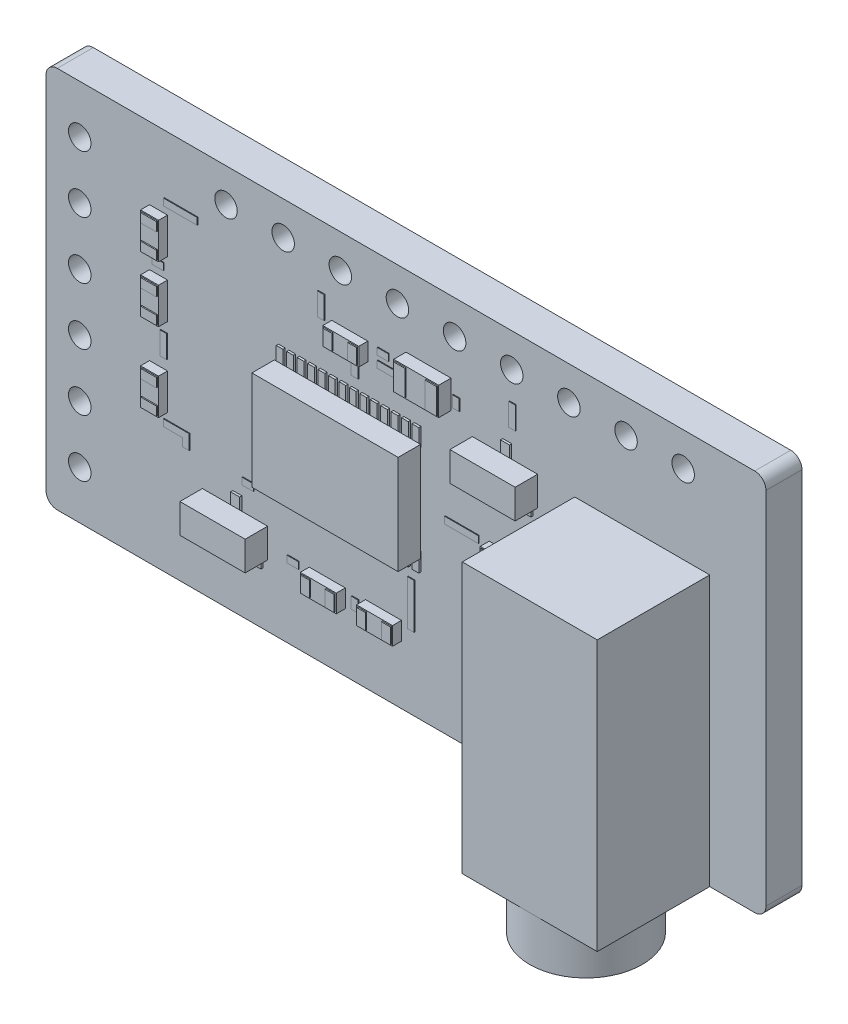
SolidWorks part; units mm, degrees
ref_plane "Front Plane" through (0, 0, 0) normal (0, 0, 1) x (1, 0, 0)
ref_plane "Top Plane" through (0, 0, 0) normal (0, 1, 0) x (1, 0, 0)
ref_plane "Right Plane" through (0, 0, 0) normal (1, 0, 0) x (0, 0, -1)
sketch "Sketch1" plane through (0, 0, 0) normal (0, 0, 1) x (1, 0, 0)
  line L0 (0.5, 0) -> (31.5, 0)
  line L1 (32, 0.5) -> (32, 16.5)
  line L2 (31.5, 17) -> (0.5, 17)
  line L3 (0, 16.5) -> (0, 0.5)
  arc A0 (31.5, 0) -> (32, 0.5) centre (31.5, 0.5) ccw
  arc A1 (32, 16.5) -> (31.5, 17) centre (31.5, 16.5) ccw
  arc A2 (0.5, 17) -> (0, 16.5) centre (0.5, 16.5) ccw
  arc A3 (0, 0.5) -> (0.5, 0) centre (0.5, 0.5) ccw
extrude "PCB" add sketch "Sketch1" along normal blind 1.6
ref_plane "Plane_z1_6" through (0, 0, 1.6) normal (0, 0, 1) x (1, 0, 0)
sketch "Sketch2" plane through (0, 0, 1.6) normal (0, 0, 1) x (1, 0, 0)
  line L0 (13.6, 11.75) -> (13.6, 12.25)
  line L1 (13.6, 12.25) -> (13.9, 12.25)
  line L2 (13.9, 12.25) -> (13.9, 11.75)
  line L3 (13.9, 11.75) -> (13.6, 11.75)
  line L4 (20.6, 13.25) -> (20.6, 14.25)
  line L5 (20.6, 14.25) -> (20.9, 14.25)
  line L6 (20.9, 14.25) -> (20.9, 13.25)
  line L7 (20.9, 13.25) -> (20.6, 13.25)
  line L8 (8.75, 5.4) -> (9.25, 5.4)
  line L9 (9.25, 5.4) -> (9.25, 5.1)
  line L10 (9.25, 5.1) -> (8.75, 5.1)
  line L11 (8.75, 5.1) -> (8.75, 5.4)
  line L12 (5.25, 5.9) -> (6.4, 5.9)
  line L13 (6.4, 5.9) -> (6.4, 5.25)
  line L14 (6.4, 5.25) -> (6.1, 5.25)
  line L15 (6.1, 5.25) -> (6.1, 5.6)
  line L16 (6.1, 5.6) -> (5.25, 5.6)
  line L17 (5.25, 5.6) -> (5.25, 5.9)
  line L18 (5.1, 8.25) -> (5.1, 9.25)
  line L19 (5.1, 9.25) -> (5.4, 9.25)
  line L20 (5.4, 9.25) -> (5.4, 8.25)
  line L21 (5.4, 8.25) -> (5.1, 8.25)
  line L22 (5.25, 11.6) -> (4.75, 11.6)
  line L23 (4.75, 11.6) -> (4.75, 11.9)
  line L24 (4.75, 11.9) -> (5.25, 11.9)
  line L25 (5.25, 11.9) -> (5.25, 11.6)
  line L26 (5.25, 14.4) -> (6.75, 14.4)
  line L27 (6.75, 14.4) -> (6.75, 14.1)
  line L28 (6.75, 14.1) -> (5.25, 14.1)
  line L29 (5.25, 14.1) -> (5.25, 14.4)
  line L30 (19.25, 8.1) -> (17.75, 8.1)
  line L31 (17.75, 8.1) -> (17.75, 8.4)
  line L32 (17.75, 8.4) -> (19.25, 8.4)
  line L33 (19.25, 8.4) -> (19.25, 8.1)
  line L34 (21.75, 8.4) -> (22.75, 8.4)
  line L35 (22.75, 8.4) -> (22.75, 8.1)
  line L36 (22.75, 8.1) -> (21.75, 8.1)
  line L37 (21.75, 8.1) -> (21.75, 8.4)
  line L38 (19.1, 6.25) -> (19.1, 7.25)
  line L39 (19.1, 7.25) -> (19.4, 7.25)
  line L40 (19.4, 7.25) -> (19.4, 6.25)
  line L41 (19.4, 6.25) -> (19.1, 6.25)
  line L42 (21.6, 6.25) -> (21.6, 7.25)
  line L43 (21.6, 7.25) -> (21.9, 7.25)
  line L44 (21.9, 7.25) -> (21.9, 6.25)
  line L45 (21.9, 6.25) -> (21.6, 6.25)
  line L46 (19.1, 4.25) -> (19.1, 5.25)
  line L47 (19.1, 5.25) -> (19.4, 5.25)
  line L48 (19.4, 5.25) -> (19.4, 4.25)
  line L49 (19.4, 4.25) -> (19.1, 4.25)
  line L50 (21.6, 4.25) -> (21.6, 5.25)
  line L51 (21.6, 5.25) -> (21.9, 5.25)
  line L52 (21.9, 5.25) -> (21.9, 4.25)
  line L53 (21.9, 4.25) -> (21.6, 4.25)
  line L54 (13.9, 3.25) -> (13.9, 2.75)
  line L55 (13.9, 2.75) -> (13.6, 2.75)
  line L56 (13.6, 2.75) -> (13.6, 3.25)
  line L57 (13.6, 3.25) -> (13.9, 3.25)
  line L58 (16.1, 3.25) -> (16.1, 5.25)
  line L59 (16.1, 5.25) -> (16.4, 5.25)
  line L60 (16.4, 5.25) -> (16.4, 3.25)
  line L61 (16.4, 3.25) -> (16.1, 3.25)
  line L62 (11.25, 3.1) -> (10.75, 3.1)
  line L63 (10.75, 3.1) -> (10.75, 3.4)
  line L64 (10.75, 3.4) -> (11.25, 3.4)
  line L65 (11.25, 3.4) -> (11.25, 3.1)
  line L66 (12.1, 13.25) -> (12.1, 14.25)
  line L67 (12.1, 14.25) -> (12.4, 14.25)
  line L68 (12.4, 14.25) -> (12.4, 13.25)
  line L69 (12.4, 13.25) -> (12.1, 13.25)
  line L70 (14.75, 13.4) -> (15.25, 13.4)
  line L71 (15.25, 13.4) -> (15.25, 13.1)
  line L72 (15.25, 13.1) -> (14.75, 13.1)
  line L73 (14.75, 13.1) -> (14.75, 13.4)
  line L74 (15.9, 13.25) -> (15.9, 12.6)
  line L75 (15.9, 12.6) -> (14.75, 12.6)
  line L76 (14.75, 12.6) -> (14.75, 12.9)
  line L77 (14.75, 12.9) -> (15.6, 12.9)
  line L78 (15.6, 12.9) -> (15.6, 13.25)
  line L79 (15.6, 13.25) -> (15.9, 13.25)
  line L80 (18.4, 13.25) -> (18.4, 12.75)
  line L81 (18.4, 12.75) -> (18.1, 12.75)
  line L82 (18.1, 12.75) -> (18.1, 13.25)
  line L83 (18.1, 13.25) -> (18.4, 13.25)
extrude "Tracks" add sketch "Sketch2" along normal blind 0.035
sketch "Sketch3" plane through (0, 0, 1.6) normal (0, 0, 1) x (1, 0, 0)
  line L1 (10.3321, 5.7) -> (10.6321, 5.7)
  line L2 (10.3321, 5.7) -> (10.3321, 6.5)
  line L3 (10.3321, 6.5) -> (10.6321, 6.5)
  line L4 (10.6321, 5.7) -> (10.6321, 6.5)
  line L6 (10.7964, 5.7) -> (11.0964, 5.7)
  line L7 (10.7964, 5.7) -> (10.7964, 6.5)
  line L8 (10.7964, 6.5) -> (11.0964, 6.5)
  line L9 (11.0964, 5.7) -> (11.0964, 6.5)
  line L11 (11.2607, 5.7) -> (11.5607, 5.7)
  line L12 (11.2607, 5.7) -> (11.2607, 6.5)
  line L13 (11.2607, 6.5) -> (11.5607, 6.5)
  line L14 (11.5607, 5.7) -> (11.5607, 6.5)
  line L16 (11.725, 5.7) -> (12.025, 5.7)
  line L17 (11.725, 5.7) -> (11.725, 6.5)
  line L18 (11.725, 6.5) -> (12.025, 6.5)
  line L19 (12.025, 5.7) -> (12.025, 6.5)
  line L21 (12.1893, 5.7) -> (12.4893, 5.7)
  line L22 (12.1893, 5.7) -> (12.1893, 6.5)
  line L23 (12.1893, 6.5) -> (12.4893, 6.5)
  line L24 (12.4893, 5.7) -> (12.4893, 6.5)
  line L26 (12.6536, 5.7) -> (12.9536, 5.7)
  line L27 (12.6536, 5.7) -> (12.6536, 6.5)
  line L28 (12.6536, 6.5) -> (12.9536, 6.5)
  line L29 (12.9536, 5.7) -> (12.9536, 6.5)
  line L31 (13.1179, 5.7) -> (13.4179, 5.7)
  line L32 (13.1179, 5.7) -> (13.1179, 6.5)
  line L33 (13.1179, 6.5) -> (13.4179, 6.5)
  line L34 (13.4179, 5.7) -> (13.4179, 6.5)
  line L36 (13.5821, 5.7) -> (13.8821, 5.7)
  line L37 (13.5821, 5.7) -> (13.5821, 6.5)
  line L38 (13.5821, 6.5) -> (13.8821, 6.5)
  line L39 (13.8821, 5.7) -> (13.8821, 6.5)
  line L41 (14.0464, 5.7) -> (14.3464, 5.7)
  line L42 (14.0464, 5.7) -> (14.0464, 6.5)
  line L43 (14.0464, 6.5) -> (14.3464, 6.5)
  line L44 (14.3464, 5.7) -> (14.3464, 6.5)
  line L46 (14.5107, 5.7) -> (14.8107, 5.7)
  line L47 (14.5107, 5.7) -> (14.5107, 6.5)
  line L48 (14.5107, 6.5) -> (14.8107, 6.5)
  line L49 (14.8107, 5.7) -> (14.8107, 6.5)
  line L51 (14.975, 5.7) -> (15.275, 5.7)
  line L52 (14.975, 5.7) -> (14.975, 6.5)
  line L53 (14.975, 6.5) -> (15.275, 6.5)
  line L54 (15.275, 5.7) -> (15.275, 6.5)
  line L56 (15.4393, 5.7) -> (15.7393, 5.7)
  line L57 (15.4393, 5.7) -> (15.4393, 6.5)
  line L58 (15.4393, 6.5) -> (15.7393, 6.5)
  line L59 (15.7393, 5.7) -> (15.7393, 6.5)
  line L61 (15.9036, 5.7) -> (16.2036, 5.7)
  line L62 (15.9036, 5.7) -> (15.9036, 6.5)
  line L63 (15.9036, 6.5) -> (16.2036, 6.5)
  line L64 (16.2036, 5.7) -> (16.2036, 6.5)
  line L66 (16.3679, 5.7) -> (16.6679, 5.7)
  line L67 (16.3679, 5.7) -> (16.3679, 6.5)
  line L68 (16.3679, 6.5) -> (16.6679, 6.5)
  line L69 (16.6679, 5.7) -> (16.6679, 6.5)
  line L71 (10.3321, 10.5) -> (10.6321, 10.5)
  line L72 (10.3321, 10.5) -> (10.3321, 11.3)
  line L73 (10.3321, 11.3) -> (10.6321, 11.3)
  line L74 (10.6321, 10.5) -> (10.6321, 11.3)
  line L76 (10.7964, 10.5) -> (11.0964, 10.5)
  line L77 (10.7964, 10.5) -> (10.7964, 11.3)
  line L78 (10.7964, 11.3) -> (11.0964, 11.3)
  line L79 (11.0964, 10.5) -> (11.0964, 11.3)
  line L81 (11.2607, 10.5) -> (11.5607, 10.5)
  line L82 (11.2607, 10.5) -> (11.2607, 11.3)
  line L83 (11.2607, 11.3) -> (11.5607, 11.3)
  line L84 (11.5607, 10.5) -> (11.5607, 11.3)
  line L86 (11.725, 10.5) -> (12.025, 10.5)
  line L87 (11.725, 10.5) -> (11.725, 11.3)
  line L88 (11.725, 11.3) -> (12.025, 11.3)
  line L89 (12.025, 10.5) -> (12.025, 11.3)
  line L91 (12.1893, 10.5) -> (12.4893, 10.5)
  line L92 (12.1893, 10.5) -> (12.1893, 11.3)
  line L93 (12.1893, 11.3) -> (12.4893, 11.3)
  line L94 (12.4893, 10.5) -> (12.4893, 11.3)
  line L96 (12.6536, 10.5) -> (12.9536, 10.5)
  line L97 (12.6536, 10.5) -> (12.6536, 11.3)
  line L98 (12.6536, 11.3) -> (12.9536, 11.3)
  line L99 (12.9536, 10.5) -> (12.9536, 11.3)
  line L101 (13.1179, 10.5) -> (13.4179, 10.5)
  line L102 (13.1179, 10.5) -> (13.1179, 11.3)
  line L103 (13.1179, 11.3) -> (13.4179, 11.3)
  line L104 (13.4179, 10.5) -> (13.4179, 11.3)
  line L106 (13.5821, 10.5) -> (13.8821, 10.5)
  line L107 (13.5821, 10.5) -> (13.5821, 11.3)
  line L108 (13.5821, 11.3) -> (13.8821, 11.3)
  line L109 (13.8821, 10.5) -> (13.8821, 11.3)
  line L111 (14.0464, 10.5) -> (14.3464, 10.5)
  line L112 (14.0464, 10.5) -> (14.0464, 11.3)
  line L113 (14.0464, 11.3) -> (14.3464, 11.3)
  line L114 (14.3464, 10.5) -> (14.3464, 11.3)
  line L116 (14.5107, 10.5) -> (14.8107, 10.5)
  line L117 (14.5107, 10.5) -> (14.5107, 11.3)
  line L118 (14.5107, 11.3) -> (14.8107, 11.3)
  line L119 (14.8107, 10.5) -> (14.8107, 11.3)
  line L121 (14.975, 10.5) -> (15.275, 10.5)
  line L122 (14.975, 10.5) -> (14.975, 11.3)
  line L123 (14.975, 11.3) -> (15.275, 11.3)
  line L124 (15.275, 10.5) -> (15.275, 11.3)
  line L126 (15.4393, 10.5) -> (15.7393, 10.5)
  line L127 (15.4393, 10.5) -> (15.4393, 11.3)
  line L128 (15.4393, 11.3) -> (15.7393, 11.3)
  line L129 (15.7393, 10.5) -> (15.7393, 11.3)
  line L131 (15.9036, 10.5) -> (16.2036, 10.5)
  line L132 (15.9036, 10.5) -> (15.9036, 11.3)
  line L133 (15.9036, 11.3) -> (16.2036, 11.3)
  line L134 (16.2036, 10.5) -> (16.2036, 11.3)
  line L136 (16.3679, 10.5) -> (16.6679, 10.5)
  line L137 (16.3679, 10.5) -> (16.3679, 11.3)
  line L138 (16.3679, 11.3) -> (16.6679, 11.3)
  line L139 (16.6679, 10.5) -> (16.6679, 11.3)
  line L141 (19.35, 10.35) -> (19.75, 10.35)
  line L142 (19.35, 10.35) -> (19.35, 11.05)
  line L143 (19.35, 11.05) -> (19.75, 11.05)
  line L144 (19.75, 10.35) -> (19.75, 11.05)
  line L146 (21.25, 10.35) -> (21.65, 10.35)
  line L147 (21.25, 10.35) -> (21.25, 11.05)
  line L148 (21.25, 11.05) -> (21.65, 11.05)
  line L149 (21.65, 10.35) -> (21.65, 11.05)
  line L151 (20.3, 11.95) -> (20.7, 11.95)
  line L152 (20.3, 11.95) -> (20.3, 12.65)
  line L153 (20.3, 12.65) -> (20.7, 12.65)
  line L154 (20.7, 11.95) -> (20.7, 12.65)
  line L156 (7.35, 2.35) -> (7.75, 2.35)
  line L157 (7.35, 2.35) -> (7.35, 3.05)
  line L158 (7.35, 3.05) -> (7.75, 3.05)
  line L159 (7.75, 2.35) -> (7.75, 3.05)
  line L161 (9.25, 2.35) -> (9.65, 2.35)
  line L162 (9.25, 2.35) -> (9.25, 3.05)
  line L163 (9.25, 3.05) -> (9.65, 3.05)
  line L164 (9.65, 2.35) -> (9.65, 3.05)
  line L166 (8.3, 3.95) -> (8.7, 3.95)
  line L167 (8.3, 3.95) -> (8.3, 4.65)
  line L168 (8.3, 4.65) -> (8.7, 4.65)
  line L169 (8.7, 3.95) -> (8.7, 4.65)
extrude "SMD_add00" add sketch "Sketch3" along normal blind 0.1
sketch "Sketch4" plane through (0, 0, 1.6) normal (0, 0, 1) x (1, 0, 0)
  line L1 (4.6, 6.2) -> (5.4, 6.2)
  line L2 (4.6, 6.2) -> (4.6, 7.8)
  line L3 (4.6, 7.8) -> (5.4, 7.8)
  line L4 (5.4, 6.2) -> (5.4, 7.8)
  line L6 (4.6, 9.7) -> (5.4, 9.7)
  line L7 (4.6, 9.7) -> (4.6, 11.3)
  line L8 (4.6, 11.3) -> (5.4, 11.3)
  line L9 (5.4, 9.7) -> (5.4, 11.3)
  line L11 (4.6, 12.2) -> (5.4, 12.2)
  line L12 (4.6, 12.2) -> (4.6, 13.8)
  line L13 (4.6, 13.8) -> (5.4, 13.8)
  line L14 (5.4, 12.2) -> (5.4, 13.8)
  line L16 (19.7, 7.6) -> (21.3, 7.6)
  line L17 (19.7, 7.6) -> (19.7, 8.4)
  line L18 (19.7, 8.4) -> (21.3, 8.4)
  line L19 (21.3, 7.6) -> (21.3, 8.4)
  line L21 (19.7, 5.6) -> (21.3, 5.6)
  line L22 (19.7, 5.6) -> (19.7, 6.4)
  line L23 (19.7, 6.4) -> (21.3, 6.4)
  line L24 (21.3, 5.6) -> (21.3, 6.4)
  line L26 (19.7, 3.6) -> (21.3, 3.6)
  line L27 (19.7, 3.6) -> (19.7, 4.4)
  line L28 (19.7, 4.4) -> (21.3, 4.4)
  line L29 (21.3, 3.6) -> (21.3, 4.4)
  line L31 (14.2, 2.6) -> (15.8, 2.6)
  line L32 (14.2, 2.6) -> (14.2, 3.4)
  line L33 (14.2, 3.4) -> (15.8, 3.4)
  line L34 (15.8, 2.6) -> (15.8, 3.4)
  line L36 (11.7, 2.6) -> (13.3, 2.6)
  line L37 (11.7, 2.6) -> (11.7, 3.4)
  line L38 (11.7, 3.4) -> (13.3, 3.4)
  line L39 (13.3, 2.6) -> (13.3, 3.4)
  line L41 (12.7, 12.6) -> (14.3, 12.6)
  line L42 (12.7, 12.6) -> (12.7, 13.4)
  line L43 (12.7, 13.4) -> (14.3, 13.4)
  line L44 (14.3, 12.6) -> (14.3, 13.4)
extrude "SMD_add01" add sketch "Sketch4" along normal blind 0.4
sketch "Sketch5" plane through (0, 0, 1.6) normal (0, 0, 1) x (1, 0, 0)
  line L1 (16, 12.575) -> (18, 12.575)
  line L2 (16, 12.575) -> (16, 13.825)
  line L3 (16, 13.825) -> (18, 13.825)
  line L4 (18, 12.575) -> (18, 13.825)
extrude "SMD_add02" add sketch "Sketch5" along normal blind 0.55
ref_plane "Plane_z1_7" through (0, 0, 1.7) normal (0, 0, 1) x (1, 0, 0)
sketch "Sketch6" plane through (0, 0, 1.7) normal (0, 0, 1) x (1, 0, 0)
  line L1 (10.25, 6.3) -> (16.75, 6.3)
  line L2 (10.25, 6.3) -> (10.25, 10.7)
  line L3 (10.25, 10.7) -> (16.75, 10.7)
  line L4 (16.75, 6.3) -> (16.75, 10.7)
  line L6 (19.05, 10.85) -> (21.95, 10.85)
  line L7 (19.05, 10.85) -> (19.05, 12.15)
  line L8 (19.05, 12.15) -> (21.95, 12.15)
  line L9 (21.95, 10.85) -> (21.95, 12.15)
  line L11 (7.05, 2.85) -> (9.95, 2.85)
  line L12 (7.05, 2.85) -> (7.05, 4.15)
  line L13 (7.05, 4.15) -> (9.95, 4.15)
  line L14 (9.95, 2.85) -> (9.95, 4.15)
extrude "SMD_add03" add sketch "Sketch6" along normal blind 1
ref_plane "Plane_z2" through (0, 0, 2) normal (0, 0, 1) x (1, 0, 0)
sketch "Sketch7" plane through (0, 0, 2) normal (0, 0, 1) x (1, 0, 0)
  line L1 (4.65, 6.25) -> (5.35, 6.25)
  line L2 (4.65, 6.25) -> (4.65, 6.65)
  line L3 (4.65, 6.65) -> (5.35, 6.65)
  line L4 (5.35, 6.25) -> (5.35, 6.65)
  line L6 (4.65, 7.35) -> (5.35, 7.35)
  line L7 (4.65, 7.35) -> (4.65, 7.75)
  line L8 (4.65, 7.75) -> (5.35, 7.75)
  line L9 (5.35, 7.35) -> (5.35, 7.75)
  line L11 (4.65, 9.75) -> (5.35, 9.75)
  line L12 (4.65, 9.75) -> (4.65, 10.15)
  line L13 (4.65, 10.15) -> (5.35, 10.15)
  line L14 (5.35, 9.75) -> (5.35, 10.15)
  line L16 (4.65, 10.85) -> (5.35, 10.85)
  line L17 (4.65, 10.85) -> (4.65, 11.25)
  line L18 (4.65, 11.25) -> (5.35, 11.25)
  line L19 (5.35, 10.85) -> (5.35, 11.25)
  line L21 (4.65, 12.25) -> (5.35, 12.25)
  line L22 (4.65, 12.25) -> (4.65, 12.65)
  line L23 (4.65, 12.65) -> (5.35, 12.65)
  line L24 (5.35, 12.25) -> (5.35, 12.65)
  line L26 (4.65, 13.35) -> (5.35, 13.35)
  line L27 (4.65, 13.35) -> (4.65, 13.75)
  line L28 (4.65, 13.75) -> (5.35, 13.75)
  line L29 (5.35, 13.35) -> (5.35, 13.75)
  line L31 (19.75, 7.65) -> (20.15, 7.65)
  line L32 (19.75, 7.65) -> (19.75, 8.35)
  line L33 (19.75, 8.35) -> (20.15, 8.35)
  line L34 (20.15, 7.65) -> (20.15, 8.35)
  line L36 (20.85, 7.65) -> (21.25, 7.65)
  line L37 (20.85, 7.65) -> (20.85, 8.35)
  line L38 (20.85, 8.35) -> (21.25, 8.35)
  line L39 (21.25, 7.65) -> (21.25, 8.35)
  line L41 (19.75, 5.65) -> (20.15, 5.65)
  line L42 (19.75, 5.65) -> (19.75, 6.35)
  line L43 (19.75, 6.35) -> (20.15, 6.35)
  line L44 (20.15, 5.65) -> (20.15, 6.35)
  line L46 (20.85, 5.65) -> (21.25, 5.65)
  line L47 (20.85, 5.65) -> (20.85, 6.35)
  line L48 (20.85, 6.35) -> (21.25, 6.35)
  line L49 (21.25, 5.65) -> (21.25, 6.35)
  line L51 (19.75, 3.65) -> (20.15, 3.65)
  line L52 (19.75, 3.65) -> (19.75, 4.35)
  line L53 (19.75, 4.35) -> (20.15, 4.35)
  line L54 (20.15, 3.65) -> (20.15, 4.35)
  line L56 (20.85, 3.65) -> (21.25, 3.65)
  line L57 (20.85, 3.65) -> (20.85, 4.35)
  line L58 (20.85, 4.35) -> (21.25, 4.35)
  line L59 (21.25, 3.65) -> (21.25, 4.35)
  line L61 (14.25, 2.65) -> (14.65, 2.65)
  line L62 (14.25, 2.65) -> (14.25, 3.35)
  line L63 (14.25, 3.35) -> (14.65, 3.35)
  line L64 (14.65, 2.65) -> (14.65, 3.35)
  line L66 (15.35, 2.65) -> (15.75, 2.65)
  line L67 (15.35, 2.65) -> (15.35, 3.35)
  line L68 (15.35, 3.35) -> (15.75, 3.35)
  line L69 (15.75, 2.65) -> (15.75, 3.35)
  line L71 (11.75, 2.65) -> (12.15, 2.65)
  line L72 (11.75, 2.65) -> (11.75, 3.35)
  line L73 (11.75, 3.35) -> (12.15, 3.35)
  line L74 (12.15, 2.65) -> (12.15, 3.35)
  line L76 (12.85, 2.65) -> (13.25, 2.65)
  line L77 (12.85, 2.65) -> (12.85, 3.35)
  line L78 (12.85, 3.35) -> (13.25, 3.35)
  line L79 (13.25, 2.65) -> (13.25, 3.35)
  line L81 (12.75, 12.65) -> (13.15, 12.65)
  line L82 (12.75, 12.65) -> (12.75, 13.35)
  line L83 (12.75, 13.35) -> (13.15, 13.35)
  line L84 (13.15, 12.65) -> (13.15, 13.35)
  line L86 (13.85, 12.65) -> (14.25, 12.65)
  line L87 (13.85, 12.65) -> (13.85, 13.35)
  line L88 (13.85, 13.35) -> (14.25, 13.35)
  line L89 (14.25, 12.65) -> (14.25, 13.35)
extrude "SMD_add04" add sketch "Sketch7" along normal blind 0.05
ref_plane "Plane_z2_15" through (0, 0, 2.15) normal (0, 0, 1) x (1, 0, 0)
sketch "Sketch8" plane through (0, 0, 2.15) normal (0, 0, 1) x (1, 0, 0)
  line L1 (16.05, 12.625) -> (16.55, 12.625)
  line L2 (16.05, 12.625) -> (16.05, 13.775)
  line L3 (16.05, 13.775) -> (16.55, 13.775)
  line L4 (16.55, 12.625) -> (16.55, 13.775)
  line L6 (17.45, 12.625) -> (17.95, 12.625)
  line L7 (17.45, 12.625) -> (17.45, 13.775)
  line L8 (17.45, 13.775) -> (17.95, 13.775)
  line L9 (17.95, 12.625) -> (17.95, 13.775)
extrude "SMD_add05" add sketch "Sketch8" along normal blind 0.05
sketch "Sketch9" plane through (0, 0, 1.6) normal (0, 0, 1) x (1, 0, 0)
  line L1 (23.5, 0) -> (29.5, 0)
  line L2 (23.5, 0) -> (23.5, 12)
  line L3 (23.5, 12) -> (29.5, 12)
  line L4 (29.5, 0) -> (29.5, 12)
extrude "Body00" add sketch "Sketch9" along normal blind 5
sketch "Sketch10" plane through (0, 0, 0) normal (0, 1, 0) x (1, 0, 0)
  circle A0 centre (26.5, -4.1) radius 2.5
extrude "Side0_J1_jack_nose" add sketch "Sketch10" against normal blind 2
sketch "Sketch11" plane through (0, 0, 0) normal (0, 1, 0) x (1, 0, 0)
  circle A0 centre (26.5, -4.1) radius 1.75
extrude "SideBore0_J1_jack_nose" cut sketch "Sketch11" against normal blind 2
sketch "Sketch12" plane through (0, 0, 1.6) normal (0, 0, 1) x (1, 0, 0)
  circle A0 centre (1.5, 2.15) radius 0.5
  circle A1 centre (1.5, 4.69) radius 0.5
  circle A2 centre (1.5, 7.23) radius 0.5
  circle A3 centre (1.5, 9.77) radius 0.5
  circle A4 centre (1.5, 12.31) radius 0.5
  circle A5 centre (1.5, 14.85) radius 0.5
  circle A6 centre (8, 15.5) radius 0.5
  circle A7 centre (10.54, 15.5) radius 0.5
  circle A8 centre (13.08, 15.5) radius 0.5
  circle A9 centre (15.62, 15.5) radius 0.5
  circle A10 centre (18.16, 15.5) radius 0.5
  circle A11 centre (20.7, 15.5) radius 0.5
  circle A12 centre (23.24, 15.5) radius 0.5
  circle A13 centre (25.78, 15.5) radius 0.5
  circle A14 centre (28.32, 15.5) radius 0.5
extrude "Holes" cut sketch "Sketch12" against normal blind 1.6
equation "\"pcb_t\" = 1.6mm"
equation "\"D1@PCB\" = \"pcb_t\""
